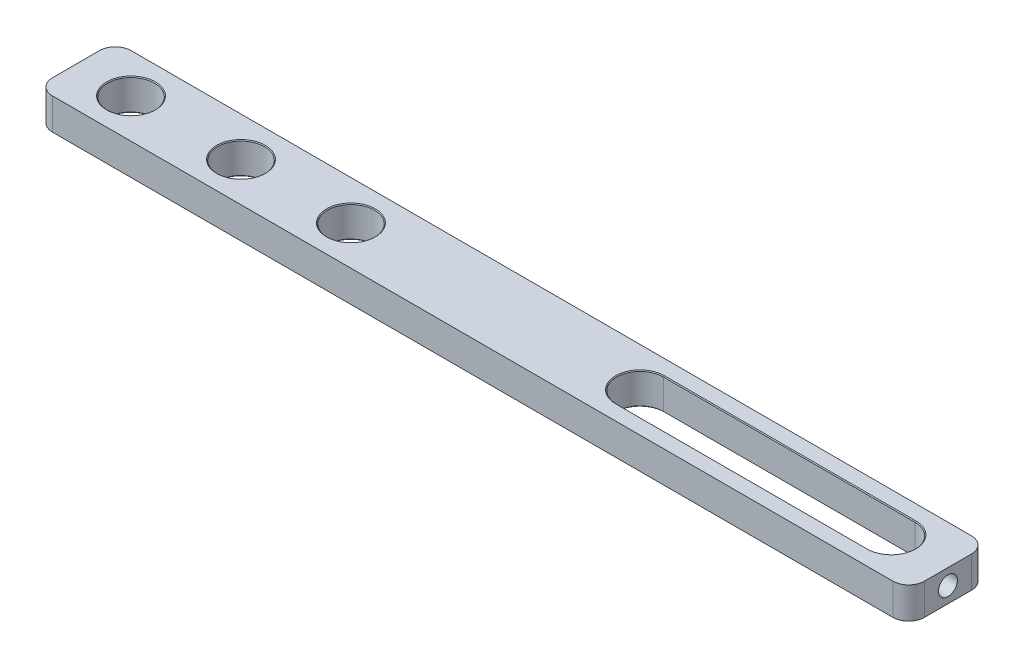
SolidWorks part; units mm, degrees
ref_plane "前视基准面" through (0, 0, 0) normal (0, 0, 1) x (1, 0, 0)
ref_plane "上视基准面" through (0, 0, 0) normal (0, 1, 0) x (1, 0, 0)
ref_plane "右视基准面" through (0, 0, 0) normal (1, 0, 0) x (0, 0, -1)
sketch "草图1" plane through (0, 0, 0) normal (0, 1, 0) x (1, 0, 0)
  line L1 (277.5, -25) -> (-277.5, -25)
  line L2 (277.5, -25) -> (277.5, 25)
  line L3 (277.5, 25) -> (-277.5, 25)
  line L4 (-277.5, -25) -> (-277.5, 25)
  line L5 (277.5, -25) -> (-277.5, 25) construction
  line L6 (277.5, 25) -> (-277.5, -25) construction
  line L9 (-277.5, 0) -> (277.5, 0) construction
  point P0 (0, 0)
  point P19 (0, 0)
  point P20 (0, 0)
  dimension "D1" = 555
  dimension "D2" = 50
extrude "凸台-拉伸1" add sketch "草图1" along normal blind 20
sketch "草图2" plane through (0, 20, 0) normal (0, 1, 0) x (1, 0, 0)
  line L0 (-277.5, 0) -> (277.5, 0) construction
  line L1 (-277.5, 25) -> (-277.5, -25) construction
  line L2 (277.5, -25) -> (277.5, 25) construction
  line L3 (81.5, 0) -> (241.5, 0) construction
  line L4 (81.5, 15) -> (241.5, 15)
  line L5 (81.5, -15) -> (241.5, -15)
  circle A0 centre (-242.5, 0) radius 15
  circle A1 centre (-172.5, 0) radius 15
  circle A2 centre (-102.5, 0) radius 15
  arc A3 (81.5, 15) -> (81.5, -15) centre (81.5, 0) ccw
  arc A4 (241.5, -15) -> (241.5, 15) centre (241.5, 0) ccw
  point P14 (161.5, 0)
  dimension "D1" = 30
  dimension "D6" = 190
  dimension "D2" = 35
  dimension "D3" = 70
  dimension "D4" = 70
  dimension "D5" = 30
  dimension "D7" = 169
extrude "切除-拉伸1" cut sketch "草图2" against normal through all
sketch "草图3" plane through (277.5, 0, 0) normal (1, 0, 0) x (0, 0, -1)
  line L0 (-25, 10) -> (25, 10) construction
  line L1 (-25, 20) -> (-25, 0) construction
  line L2 (25, 20) -> (25, 0) construction
  line L3 (0, 20) -> (0, 0) construction
  line L4 (-25, 20) -> (25, 20) construction
  circle A0 centre (0, 10) radius 6
  dimension "D1" = 12
extrude "切除-拉伸2" cut sketch "草图3" against normal up to next
fillet "圆角1" radius 10 4 edges at (-277.5, 10, -25) (-277.5, 10, 25) (277.5, 10, -25) (277.5, 10, 25)
chamfer "倒角1" distance 0.5 14 edges at (-102.5, 20, 15) (-102.5, 0, 15) (161.5, 0, 15) (256.5, 0, 0) (66.5, 0, 0) (161.5, 0, -15) (161.5, 20, 15) (256.5, 20, 0) (66.5, 20, 0) (161.5, 20, -15) (-172.5, 0, 15) (-172.5, 20, 15) (-242.5, 0, 15) (-242.5, 20, 15)
